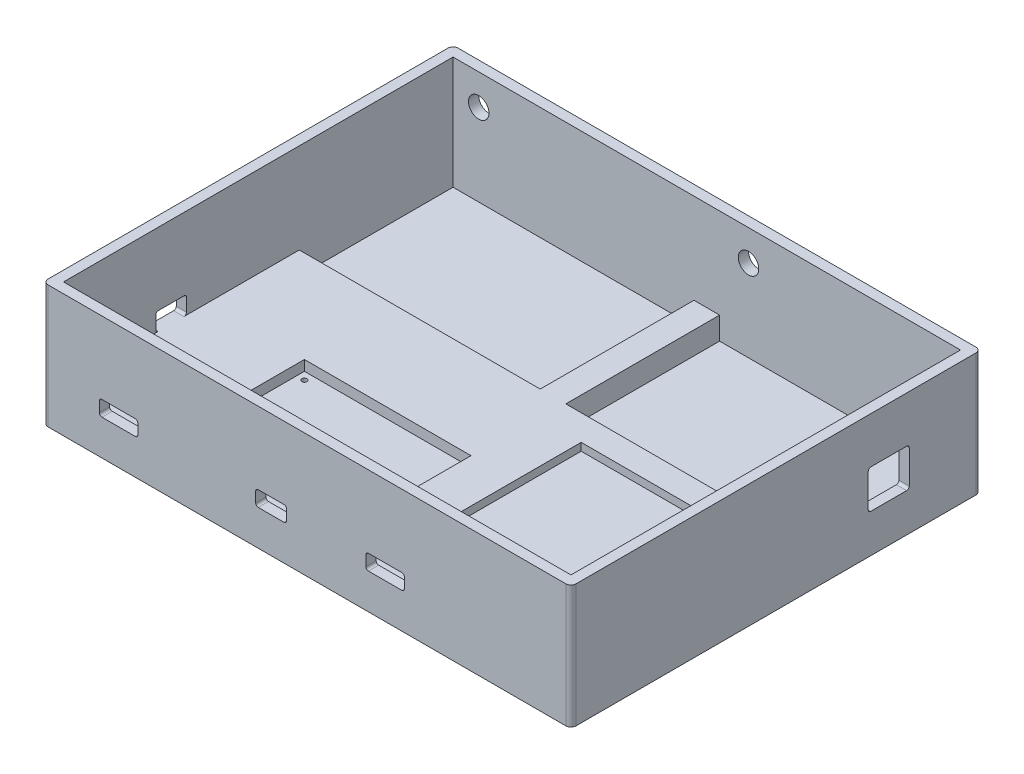
SolidWorks part; units mm, degrees
ref_plane "Front Plane" through (0, 0, 0) normal (0, 0, 1) x (1, 0, 0)
ref_plane "Top Plane" through (0, 0, 0) normal (0, 1, 0) x (1, 0, 0)
ref_plane "Right Plane" through (0, 0, 0) normal (1, 0, 0) x (0, 0, -1)
sketch "Sketch1" plane through (0, 0, 0) normal (0, 1, 0) x (1, 0, 0)
  line L1 (0, 0) -> (261.62, 0)
  line L2 (0, 0) -> (0, 203.2)
  line L3 (0, 203.2) -> (261.62, 203.2)
  line L4 (261.62, 0) -> (261.62, 203.2)
  dimension "D1" = 203.2
  dimension "D2" = 261.62
extrude "Boss-Extrude1" add sketch "Sketch1" along normal blind 5.08
sketch "Sketch4" plane through (0, 5.08, 0) normal (0, 1, 0) x (1, 0, 0)
  line L0 (0, 0) -> (5.08, 0)
  line L1 (0, 0) -> (261.62, 0) construction
  line L2 (5.08, 0) -> (5.08, 198.12)
  line L3 (5.08, 198.12) -> (256.54, 198.12)
  line L4 (256.54, 198.12) -> (256.54, 0)
  line L5 (256.54, 0) -> (261.62, 0)
  line L6 (261.62, 0) -> (261.62, 203.2)
  line L7 (261.62, 203.2) -> (0, 203.2)
  line L8 (0, 203.2) -> (0, 0)
  dimension "D1" = 5.08
  dimension "D2" = 5.08
  dimension "D3" = 5.08
extrude "Boss-Extrude3" add sketch "Sketch4" along normal blind 55.88
sketch "Sketch5" plane through (0, 5.08, 0) normal (0, 1, 0) x (1, 0, 0)
  line L0 (5.08, 121.92) -> (124.46, 121.92)
  line L1 (5.08, 0) -> (5.08, 198.12) construction
  line L2 (124.46, 121.92) -> (124.46, 198.12)
  line L3 (5.08, 198.12) -> (256.54, 198.12) construction
  line L4 (124.46, 198.12) -> (137.16, 198.12)
  line L5 (137.16, 198.12) -> (137.16, 121.92)
  line L6 (137.16, 121.92) -> (256.54, 121.92)
  line L7 (256.54, 198.12) -> (256.54, 0) construction
  line L8 (256.54, 121.92) -> (256.54, 116.84)
  line L9 (256.54, 116.84) -> (5.08, 116.84)
  line L10 (5.08, 116.84) -> (5.08, 121.92)
  line L11 (5.08, 198.12) -> (256.54, 198.12) construction
  line L12 (256.54, 198.12) -> (256.54, 0) construction
  dimension "D1" = 5.08
  dimension "D2" = 5.08
  dimension "D3" = 76.2
  dimension "D4" = 119.38
  dimension "D5" = 119.38
extrude "Boss-Extrude4" add sketch "Sketch5" along normal blind 11.176 contours L2 L4 L5 L6 L8 L9 L10 L0
sketch "Sketch7" plane through (0, 5.08, 0) normal (0, 1, 0) x (1, 0, 0)
  line L1 (5.08, 116.84) -> (256.54, 116.84)
  line L2 (5.08, 116.84) -> (5.08, 0)
  line L3 (5.08, 0) -> (256.54, 0)
  line L4 (256.54, 116.84) -> (256.54, 0)
extrude "Boss-Extrude5" add sketch "Sketch7" along normal blind 11.176
sketch "Sketch8" plane through (0, 0, -198.12) normal (0, 0, 1) x (1, 0, 0)
  line L0 (0, 0) -> (261.62, 0) construction
  line L1 (5.08, 60.96) -> (5.08, 16.256) construction
  line L2 (256.54, 60.96) -> (256.54, 5.08) construction
  circle A0 centre (17.78, 45.72) radius 5.08
  circle A1 centre (151.4856, 45.72) radius 5.08
  dimension "D1" = 10.16
  dimension "D4" = 10.16
  dimension "D6" = 105.0544
  dimension "D2" = 45.72
  dimension "D3" = 12.7
  dimension "D5" = 45.72
extrude "Cut-Extrude2" cut sketch "Sketch8" against normal blind 11.176
sketch "Sketch9" plane through (5.08, 0, 0) normal (1, 0, 0) x (0, 0, -1)
  line L0 (0, 16.256) -> (121.92, 16.256) construction
  line L1 (52.07, 16.256) -> (64.77, 16.256)
  line L2 (50.8, 17.526) -> (50.8, 23.876)
  line L3 (52.07, 25.146) -> (64.77, 25.146)
  line L4 (66.04, 17.526) -> (66.04, 23.876)
  arc A0 (52.07, 16.256) -> (50.8, 17.526) centre (52.07, 17.526) cw
  arc A1 (64.77, 16.256) -> (66.04, 17.526) centre (64.77, 17.526) ccw
  arc A2 (64.77, 25.146) -> (66.04, 23.876) centre (64.77, 23.876) cw
  arc A3 (50.8, 23.876) -> (52.07, 25.146) centre (52.07, 23.876) cw
  point P10 (50.8, 16.256)
  point P13 (66.04, 16.256)
  point P18 (50.8, 25.146)
  dimension "D4" = 1.27
  dimension "D1" = 8.89
  dimension "D2" = 15.24
  dimension "D3" = 55.88
extrude "Cut-Extrude3" cut sketch "Sketch9" against normal blind 11.176
sketch "Sketch10" plane through (0, 16.256, 0) normal (0, 1, 0) x (1, 0, 0)
  line L0 (5.08, 64.77) -> (5.08, 121.92) construction
  line L1 (53.34, 76.2) -> (135.89, 76.2)
  line L2 (53.34, 76.2) -> (53.34, 16.51)
  line L3 (53.34, 16.51) -> (135.89, 16.51)
  line L4 (135.89, 76.2) -> (135.89, 16.51)
  line L6 (5.08, 121.92) -> (124.46, 121.92) construction
  dimension "D1" = 82.55
  dimension "D2" = 59.69
  dimension "D3" = 48.26
  dimension "D4" = 45.72
extrude "Cut-Extrude4" cut sketch "Sketch10" against normal blind 5.08
sketch "Sketch12" plane through (0, 11.176, 0) normal (0, 1, 0) x (1, 0, 0)
  line L0 (135.89, 76.2) -> (53.34, 76.2) construction
  line L1 (53.34, 76.2) -> (53.34, 16.51) construction
  line L2 (53.34, 16.51) -> (135.89, 16.51) construction
  circle A0 centre (57.15, 72.39) radius 1.27
  circle A1 centre (57.15, 20.32) radius 1.27
  dimension "D1" = 2.54
  dimension "D2" = 2.54
  dimension "D4" = 3.81
  dimension "D5" = 3.81
  dimension "D6" = 3.81
  dimension "D3" = 3.81
extrude "Cut-Extrude5" cut sketch "Sketch12" against normal blind 8.89
sketch "Sketch13" plane through (0, 16.256, 0) normal (0, 1, 0) x (1, 0, 0)
  line L1 (157.48, 109.22) -> (254, 109.22)
  line L2 (157.48, 109.22) -> (157.48, 43.18)
  line L3 (157.48, 43.18) -> (254, 43.18)
  line L4 (254, 109.22) -> (254, 43.18)
  line L5 (137.16, 121.92) -> (256.54, 121.92) construction
  line L6 (256.54, 121.92) -> (256.54, 0) construction
  dimension "D1" = 96.52
  dimension "D2" = 66.04
  dimension "D3" = 2.54
  dimension "D4" = 12.7
extrude "Cut-Extrude6" cut sketch "Sketch13" against normal blind 3.81
sketch "Sketch14" plane through (0, 16.256, 0) normal (0, 1, 0) x (1, 0, 0)
  line L0 (5.08, 0) -> (256.54, 0) construction
  line L1 (5.08, 0) -> (256.54, 0)
  line L2 (5.08, 0) -> (5.08, 5.08)
  line L3 (5.08, 5.08) -> (256.54, 5.08)
  line L4 (256.54, 0) -> (256.54, 5.08)
  line L5 (0, 0) -> (5.08, 0) construction
  line L6 (256.54, 198.12) -> (256.54, 0) construction
  dimension "D1" = 5.08
extrude "Boss-Extrude6" add sketch "Sketch14" along normal blind 44.704
sketch "Sketch15" plane through (0, 0, -5.08) normal (0, 0, -1) x (-1, 0, 0)
  line L0 (-135.89, 11.176) -> (-135.89, 16.256) construction
  line L1 (-106.68, 17.526) -> (-119.38, 17.526)
  line L2 (-105.41, 18.796) -> (-105.41, 23.876)
  line L3 (-106.68, 25.146) -> (-119.38, 25.146)
  line L4 (-120.65, 18.796) -> (-120.65, 23.876)
  line L5 (-256.54, 16.256) -> (-5.08, 16.256) construction
  arc A0 (-105.41, 23.876) -> (-106.68, 25.146) centre (-106.68, 23.876) ccw
  arc A1 (-106.68, 17.526) -> (-105.41, 18.796) centre (-106.68, 18.796) ccw
  arc A2 (-119.38, 17.526) -> (-120.65, 18.796) centre (-119.38, 18.796) cw
  arc A3 (-119.38, 25.146) -> (-120.65, 23.876) centre (-119.38, 23.876) ccw
  point P6 (-105.41, 25.146)
  point P9 (-105.41, 17.526)
  point P12 (-120.65, 17.526)
  dimension "D3" = 1.27
  dimension "D1" = 15.24
  dimension "D2" = 7.62
  dimension "D4" = 15.24
  dimension "D5" = 1.27
extrude "Cut-Extrude7" cut sketch "Sketch15" against normal blind 39.624
sketch "Sketch16" plane through (0, 0, 0) normal (0, 0, 1) x (1, 0, 0)
  line L0 (161.29, 25.146) -> (177.8, 25.146)
  line L1 (29.21, 25.146) -> (45.72, 25.146)
  line L2 (27.94, 23.876) -> (27.94, 18.796)
  line L3 (29.21, 17.526) -> (45.72, 17.526)
  line L4 (46.99, 23.876) -> (46.99, 18.796)
  line L5 (160.02, 23.876) -> (160.02, 18.796)
  line L6 (161.29, 17.526) -> (177.8, 17.526)
  line L7 (179.07, 23.876) -> (179.07, 18.796)
  line L8 (5.08, 60.96) -> (5.08, 5.08) construction
  line L10 (256.54, 16.256) -> (5.08, 16.256) construction
  line L11 (137.16, 16.256) -> (137.16, 5.08) construction
  arc A0 (45.72, 25.146) -> (46.99, 23.876) centre (45.72, 23.876) cw
  arc A1 (45.72, 17.526) -> (46.99, 18.796) centre (45.72, 18.796) ccw
  arc A2 (27.94, 18.796) -> (29.21, 17.526) centre (29.21, 18.796) ccw
  arc A3 (29.21, 25.146) -> (27.94, 23.876) centre (29.21, 23.876) ccw
  arc A4 (177.8, 25.146) -> (179.07, 23.876) centre (177.8, 23.876) cw
  arc A5 (177.8, 17.526) -> (179.07, 18.796) centre (177.8, 18.796) ccw
  arc A6 (160.02, 18.796) -> (161.29, 17.526) centre (161.29, 18.796) ccw
  arc A7 (161.29, 25.146) -> (160.02, 23.876) centre (161.29, 23.876) ccw
  point P6 (46.99, 25.146)
  point P9 (46.99, 17.526)
  point P12 (27.94, 17.526)
  dimension "D3" = 1.27
  dimension "D10" = 1.27
  dimension "D1" = 19.05
  dimension "D2" = 7.62
  dimension "D4" = 22.86
  dimension "D5" = 1.27
  dimension "D6" = 1.27
  dimension "D7" = 19.05
  dimension "D8" = 7.62
  dimension "D9" = 22.86
extrude "Cut-Extrude8" cut sketch "Sketch16" against normal blind 39.624
sketch "Sketch17" plane through (256.54, 0, 0) normal (-1, 0, 0) x (0, 0, 1)
  line L0 (-198.12, 60.96) -> (-198.12, 5.08) construction
  line L1 (-166.37, 38.1) -> (-148.59, 38.1)
  line L2 (-167.64, 36.83) -> (-167.64, 20.32)
  line L3 (-166.37, 19.05) -> (-148.59, 19.05)
  line L4 (-147.32, 36.83) -> (-147.32, 20.32)
  line L5 (-198.12, 5.08) -> (-121.92, 5.08) construction
  arc A0 (-148.59, 19.05) -> (-147.32, 20.32) centre (-148.59, 20.32) ccw
  arc A1 (-148.59, 38.1) -> (-147.32, 36.83) centre (-148.59, 36.83) cw
  arc A2 (-167.64, 20.32) -> (-166.37, 19.05) centre (-166.37, 20.32) ccw
  arc A3 (-166.37, 38.1) -> (-167.64, 36.83) centre (-166.37, 36.83) ccw
  point P12 (-147.32, 38.1)
  point P17 (-167.64, 38.1)
  dimension "D5" = 1.27
  dimension "D1" = 20.32
  dimension "D2" = 19.05
  dimension "D3" = 30.48
  dimension "D4" = 13.97
extrude "Cut-Extrude9" cut sketch "Sketch17" against normal blind 39.624
fillet "Fillet1" radius 2.54 4 edges at (0, 30.48, 0) (0, 30.48, -203.2) (261.62, 30.48, -203.2) (261.62, 30.48, 0)
